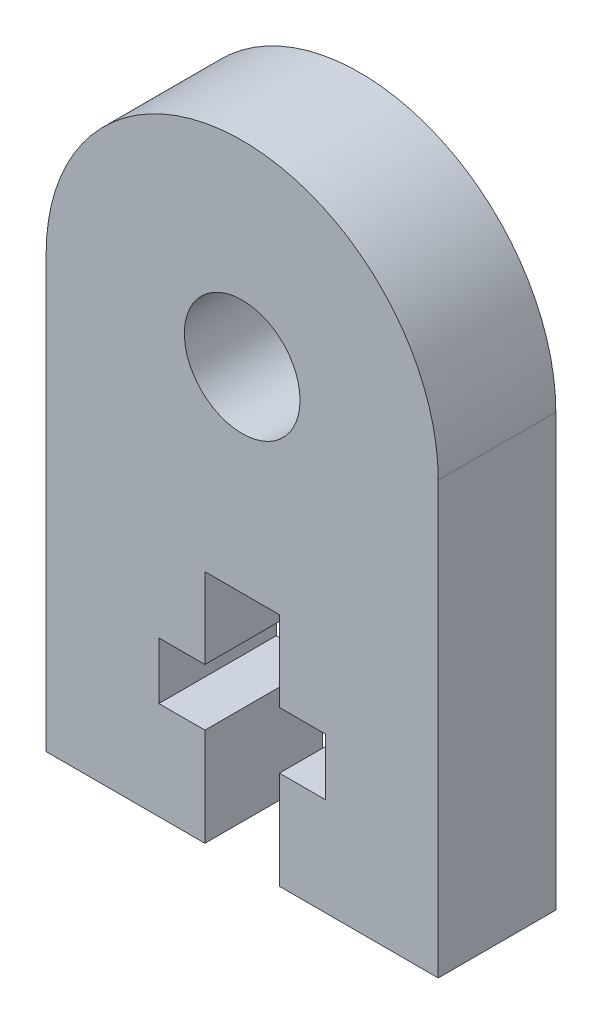
SolidWorks part; units mm, degrees
material "ABS"
ref_plane "Front Plane" through (0, 0, 0) normal (0, 0, 1) x (1, 0, 0)
ref_plane "Top Plane" through (0, 0, 0) normal (0, 1, 0) x (1, 0, 0)
ref_plane "Right Plane" through (0, 0, 0) normal (1, 0, 0) x (0, 0, -1)
sketch "Sketch1" plane through (0, 0, 0) normal (0, 0, 1) x (1, 0, 0)
  line L0 (0, 0) -> (-2.086, 2.086) construction
  line L1 (0, 0) -> (0, 2.95) construction
  line L2 (-10, 0) -> (-10, -22)
  line L3 (-10, -22) -> (10, -22)
  line L4 (10, -22) -> (10, 0)
  line L5 (0, 0) -> (0, -22) construction
  circle A0 centre (0, 0) radius 2.95
  arc A1 (-10, 0) -> (10, 0) centre (0, 0) cw
  dimension "D1" = 5.9
  dimension "D4" = 45
  dimension "D5" = 22
  dimension "D6" = 20
extrude "Boss-Extrude1" add sketch "Sketch1" along normal blind 6
sketch "Sketch3" plane through (0, 0, 6) normal (0, 0, 1) x (1, 0, 0)
  line L0 (-10, -22) -> (10, -22) construction
  line L1 (-1.9, -22) -> (1.9, -22)
  line L2 (-1.9, -22) -> (-1.9, -17)
  line L3 (-1.9, -10) -> (1.9, -10)
  line L4 (1.9, -22) -> (1.9, -17)
  line L5 (0, -10) -> (0, 0) construction
  line L6 (1.9, -14.1) -> (4.25, -14.1)
  line L7 (-4.25, -14.1) -> (-1.9, -14.1)
  line L8 (-4.25, -14.1) -> (-4.25, -17)
  line L9 (-4.25, -17) -> (-1.9, -17)
  line L10 (4.25, -14.1) -> (4.25, -17)
  line L11 (-1.9, -14.1) -> (-1.9, -10)
  line L12 (1.9, -17) -> (4.25, -17)
  line L13 (1.9, -14.1) -> (1.9, -10)
  point P18 (-3.075, -17)
  dimension "D1" = 3.8
  dimension "D3" = 12
  dimension "D4" = 8.5
  dimension "D5" = 2.9
  dimension "D6" = 5
extrude "Cut-Extrude2" cut sketch "Sketch3" against normal through all
equation "\"smallPulleyTeeth\"= 30"
equation "\"largePulleyTeeth\"= 30"
equation "\"eighthThick\"= 3.0mm"
equation "\"sixteenthThick\"= 1.7mm"
equation "\"quarterThick\"=6.0mm"
equation "\"OD\"= 145mm"
equation "\"puckAngle\"= 60.5deg"
equation "\"puckDiam\"= 76.5mm"
equation "\"axlePress\"= 5.9mm"
equation "\"D1@Sketch1\"=\"axlePress\""
equation "\"D1@Boss-Extrude1\"=\"quarterThick\""
equation "\"press\"= 0.2mm"
equation "\"wheelClear\"= 0.3mm"
equation "\"10-32clear\"= 4.8mm"
equation "\"D1@Sketch3\"=\"8-32clear\"-\"press\""
equation "\"6-32clear\"= 3.3mm"
equation "\"8-32clear\"= 4.0mm"
equation "\"wheelHeight\"= 22mm"
equation "\"D5@Sketch1\"=\"wheelHeight\""
equation "\"wheelWell\"= 65mm"
